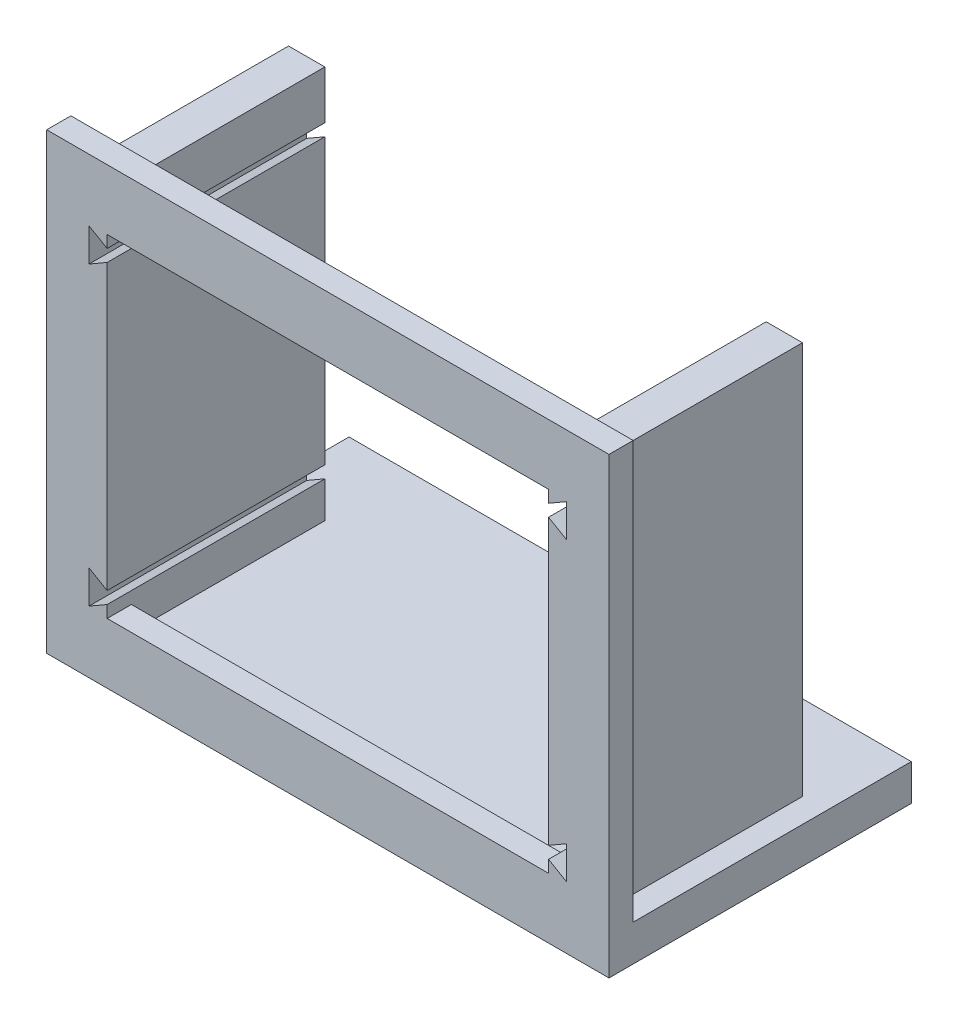
SolidWorks part; units mm, degrees
ref_plane "Front Plane" through (0, 0, 0) normal (0, 0, 1) x (1, 0, 0)
ref_plane "Top Plane" through (0, 0, 0) normal (0, 1, 0) x (1, 0, 0)
ref_plane "Right Plane" through (0, 0, 0) normal (1, 0, 0) x (0, 0, -1)
sketch "Sketch2" plane through (0, 0, 0) normal (0, 1, 0) x (1, 0, 0)
  line L1 (-100, 75) -> (100, 75)
  line L2 (-100, 75) -> (-100, -75)
  line L3 (-100, -75) -> (100, -75)
  line L4 (100, 75) -> (100, -75)
  line L5 (-100, 75) -> (100, -75) construction
  line L6 (-100, -75) -> (100, 75) construction
  point P0 (0, 0)
  dimension "D1" = 200
  dimension "D2" = 150
extrude "Boss-Extrude1" add sketch "Sketch2" along normal blind 80
fillet "Fillet1" radius 10 4 edges at (-100, 40, -75) (100, 40, -75) (100, 40, 75) (-100, 40, 75)
shell "Shell1" thickness 2
sketch "Sketch5" plane through (0, 0, 75) normal (0, 0, 1) x (1, 0, 0)
  line L1 (-18.25, 44.5) -> (18.25, 44.5)
  line L2 (-18.25, 44.5) -> (-18.25, 17)
  line L3 (-18.25, 17) -> (18.25, 17)
  line L4 (18.25, 44.5) -> (18.25, 17)
  line L5 (-18.25, 43.5) -> (-19.75, 44.366)
  line L6 (-19.75, 44.366) -> (-19.75, 41.634)
  line L7 (-19.75, 41.634) -> (-18.25, 42.5)
  line L8 (-18.25, 42.5) -> (-18.25, 43.5)
  line L9 (0, 44.5) -> (0, 17) construction
  line L10 (-18.25, 30.75) -> (18.25, 30.75) construction
  line L11 (-19.75, 19.866) -> (-18.25, 19)
  line L12 (-19.75, 17.134) -> (-19.75, 19.866)
  line L13 (-18.25, 18) -> (-19.75, 17.134)
  line L14 (-18.25, 19) -> (-18.25, 18)
  line L15 (19.75, 17.134) -> (19.75, 19.866)
  line L16 (18.25, 18) -> (19.75, 17.134)
  line L17 (18.25, 19) -> (18.25, 18)
  line L18 (19.75, 19.866) -> (18.25, 19)
  line L19 (19.75, 41.634) -> (18.25, 42.5)
  line L20 (19.75, 44.366) -> (19.75, 41.634)
  line L21 (18.25, 43.5) -> (19.75, 44.366)
  line L22 (18.25, 42.5) -> (18.25, 43.5)
  line L23 (-90, 15) -> (90, 15) construction
  point P4 (0, 17)
  dimension "D1" = 36.5
  dimension "D2" = 27.5
  dimension "D3" = 60
  dimension "D4" = 60
  dimension "D5" = 1
  dimension "D6" = 1
  dimension "D7" = 1.5
  dimension "D8" = 2
extrude "Cut-Extrude1" cut sketch "Sketch5" against normal up to surface (2 mm away) contours L1 L4 L3 L2 | L7 L8 L5 L6 | L12 L11 L14 L13 | L20 L19 L22 L21 | L15 L18 L17 L16 up to face at (0, 47.5, 73)
sketch "Sketch6" plane through (0, 0, 73) normal (0, 0, -1) x (-1, 0, 0)
  line L0 (18.25, 15) -> (21.25, 15)
  line L2 (-21.25, 47.5) -> (-21.25, 15)
  line L4 (19.75, 44.366) -> (18.25, 43.5)
  line L5 (19.75, 41.634) -> (19.75, 44.366)
  line L6 (18.25, 42.5) -> (19.75, 41.634)
  line L7 (18.25, 43.5) -> (18.25, 42.5)
  line L8 (19.75, 44.366) -> (18.25, 43.5)
  line L9 (19.75, 41.634) -> (19.75, 44.366)
  line L10 (18.25, 42.5) -> (19.75, 41.634)
  line L12 (18.25, 44.5) -> (-18.25, 44.5)
  line L13 (-18.25, 44.5) -> (-18.25, 17)
  line L14 (-18.25, 17) -> (18.25, 17)
  line L15 (18.25, 17) -> (18.25, 44.5)
  line L17 (-18.25, 47.5) -> (-18.25, 43.5)
  line L19 (18.25, 15) -> (18.25, 18)
  line L20 (-19.75, 41.634) -> (-18.25, 42.5)
  line L21 (-18.25, 42.5) -> (-18.25, 43.5)
  line L22 (-18.25, 43.5) -> (-19.75, 44.366)
  line L23 (-19.75, 44.366) -> (-19.75, 41.634)
  line L24 (-19.75, 41.634) -> (-18.25, 42.5)
  line L26 (-18.25, 43.5) -> (-19.75, 44.366)
  line L27 (-19.75, 44.366) -> (-19.75, 41.634)
  line L28 (-19.75, 19.866) -> (-19.75, 17.134)
  line L29 (-18.25, 19) -> (-19.75, 19.866)
  line L30 (-18.25, 18) -> (-18.25, 19)
  line L31 (-19.75, 17.134) -> (-18.25, 18)
  line L32 (-19.75, 19.866) -> (-19.75, 17.134)
  line L33 (-18.25, 19) -> (-19.75, 19.866)
  line L35 (-19.75, 17.134) -> (-18.25, 18)
  line L36 (19.75, 19.866) -> (18.25, 19)
  line L37 (18.25, 19) -> (18.25, 18)
  line L38 (18.25, 18) -> (19.75, 17.134)
  line L39 (19.75, 17.134) -> (19.75, 19.866)
  line L40 (19.75, 19.866) -> (18.25, 19)
  line L42 (18.25, 18) -> (19.75, 17.134)
  line L43 (19.75, 17.134) -> (19.75, 19.866)
  line L44 (21.25, 47.5) -> (21.25, 15)
  line L45 (-18.25, 15) -> (-21.25, 15)
  line L46 (-18.25, 42.5) -> (-18.25, 19)
  line L47 (18.25, 43.5) -> (18.25, 47.5)
  line L48 (18.25, 19) -> (18.25, 42.5)
  line L49 (-18.25, 18) -> (-18.25, 15)
  line L50 (21.25, 47.5) -> (18.25, 47.5)
  line L51 (-21.25, 47.5) -> (-18.25, 47.5)
  line L54 (18.25, 44.5) -> (-18.25, 44.5) construction
  line L55 (90, 15) -> (-90, 15) construction
  dimension "D6" = 3
  dimension "D7" = 3
  dimension "D8" = 3
  dimension "D1" = 0
  dimension "D2" = 0
  dimension "D3" = 0
  dimension "D4" = 0
  dimension "D5" = 0
extrude "Boss-Extrude2" add sketch "Sketch6" along normal blind 16
sketch "Sketch7" plane through (100, 0, 0) normal (1, 0, 0) x (0, 0, -1)
  line L0 (-65, 15) -> (65, 15) construction
  line L1 (-18.25, 44.5) -> (18.25, 44.5)
  line L2 (-18.25, 44.5) -> (-18.25, 17)
  line L3 (-18.25, 17) -> (18.25, 17)
  line L4 (18.25, 44.5) -> (18.25, 17)
  line L5 (-18.25, 43.5) -> (-19.75, 44.366)
  line L6 (-19.75, 44.366) -> (-19.75, 41.634)
  line L7 (-19.75, 41.634) -> (-18.25, 42.5)
  line L8 (-18.25, 42.5) -> (-18.25, 43.5)
  line L9 (0, 44.5) -> (0, 17) construction
  line L10 (-18.25, 30.75) -> (18.25, 30.75) construction
  line L11 (-19.75, 19.866) -> (-18.25, 19)
  line L12 (-19.75, 17.134) -> (-19.75, 19.866)
  line L13 (-18.25, 18) -> (-19.75, 17.134)
  line L14 (-18.25, 19) -> (-18.25, 18)
  line L15 (19.75, 17.134) -> (19.75, 19.866)
  line L16 (18.25, 18) -> (19.75, 17.134)
  line L17 (18.25, 19) -> (18.25, 18)
  line L18 (19.75, 19.866) -> (18.25, 19)
  line L19 (19.75, 41.634) -> (18.25, 42.5)
  line L20 (19.75, 44.366) -> (19.75, 41.634)
  line L21 (18.25, 43.5) -> (19.75, 44.366)
  line L22 (18.25, 42.5) -> (18.25, 43.5)
  dimension "D1" = 36.5
  dimension "D2" = 27.5
  dimension "D3" = 60
  dimension "D4" = 60
  dimension "D5" = 1
  dimension "D6" = 1
  dimension "D7" = 1.5
  dimension "D8" = 2
extrude "Cut-Extrude2" cut sketch "Sketch7" against normal blind 2 contours L1 L4 L3 L2 | L7 L8 L5 L6 | L12 L11 L14 L13 | L20 L19 L22 L21 | L15 L18 L17 L16
sketch "Sketch8" plane through (98, 0, 0) normal (-1, 0, 0) x (0, 0, 1)
  line L0 (65, 15) -> (-65, 15) construction
  line L1 (-21.25, 47.5) -> (-18.25, 47.5)
  line L2 (-21.25, 47.5) -> (-21.25, 15)
  line L3 (-21.25, 15) -> (-18.25, 15)
  line L4 (19.75, 44.366) -> (18.25, 43.5)
  line L5 (19.75, 41.634) -> (19.75, 44.366)
  line L6 (18.25, 42.5) -> (19.75, 41.634)
  line L7 (18.25, 43.5) -> (18.25, 42.5)
  line L8 (19.75, 44.366) -> (18.25, 43.5)
  line L9 (19.75, 41.634) -> (19.75, 44.366)
  line L10 (18.25, 42.5) -> (19.75, 41.634)
  line L20 (-19.75, 41.634) -> (-18.25, 42.5)
  line L21 (-18.25, 42.5) -> (-18.25, 43.5)
  line L22 (-18.25, 43.5) -> (-19.75, 44.366)
  line L23 (-19.75, 44.366) -> (-19.75, 41.634)
  line L24 (-19.75, 41.634) -> (-18.25, 42.5)
  line L26 (-18.25, 43.5) -> (-19.75, 44.366)
  line L27 (-19.75, 44.366) -> (-19.75, 41.634)
  line L28 (-19.75, 19.866) -> (-19.75, 17.134)
  line L29 (-18.25, 19) -> (-19.75, 19.866)
  line L30 (-18.25, 18) -> (-18.25, 19)
  line L31 (-19.75, 17.134) -> (-18.25, 18)
  line L32 (-19.75, 19.866) -> (-19.75, 17.134)
  line L33 (-18.25, 19) -> (-19.75, 19.866)
  line L35 (-19.75, 17.134) -> (-18.25, 18)
  line L36 (19.75, 19.866) -> (18.25, 19)
  line L37 (18.25, 19) -> (18.25, 18)
  line L38 (18.25, 18) -> (19.75, 17.134)
  line L39 (19.75, 17.134) -> (19.75, 19.866)
  line L40 (19.75, 19.866) -> (18.25, 19)
  line L42 (18.25, 18) -> (19.75, 17.134)
  line L43 (19.75, 17.134) -> (19.75, 19.866)
  line L44 (-18.25, 47.5) -> (-18.25, 43.5)
  line L46 (-18.25, 42.5) -> (-18.25, 19) construction
  line L47 (18.25, 44.5) -> (-18.25, 44.5) construction
  line L48 (-18.25, 42.5) -> (-18.25, 19)
  line L49 (-18.25, 18) -> (-18.25, 15)
  line L50 (18.25, 42.5) -> (18.25, 19) construction
  line L51 (18.25, 47.5) -> (21.25, 47.5)
  line L52 (18.25, 47.5) -> (18.25, 43.5)
  line L53 (18.25, 15) -> (21.25, 15)
  line L54 (21.25, 47.5) -> (21.25, 15)
  line L55 (18.25, 42.5) -> (18.25, 19)
  line L56 (18.25, 18) -> (18.25, 15)
  dimension "D6" = 3
  dimension "D7" = 3
  dimension "D2" = 3
  dimension "D1" = 0
  dimension "D3" = 0
  dimension "D4" = 0
  dimension "D5" = 0
extrude "Boss-Extrude3" add sketch "Sketch8" along normal blind 16
sketch "Sketch10" plane through (-100, 0, 0) normal (-1, 0, 0) x (0, 0, 1)
  line L1 (-18.25, 44.5) -> (18.25, 44.5)
  line L2 (-18.25, 44.5) -> (-18.25, 17)
  line L3 (-18.25, 17) -> (18.25, 17)
  line L4 (18.25, 44.5) -> (18.25, 17)
  line L5 (-18.25, 43.5) -> (-19.75, 44.366)
  line L6 (-19.75, 44.366) -> (-19.75, 41.634)
  line L7 (-19.75, 41.634) -> (-18.25, 42.5)
  line L8 (-18.25, 42.5) -> (-18.25, 43.5)
  line L9 (0, 44.5) -> (0, 17) construction
  line L10 (-18.25, 30.75) -> (18.25, 30.75) construction
  line L11 (-19.75, 19.866) -> (-18.25, 19)
  line L12 (-19.75, 17.134) -> (-19.75, 19.866)
  line L13 (-18.25, 18) -> (-19.75, 17.134)
  line L14 (-18.25, 19) -> (-18.25, 18)
  line L15 (19.75, 17.134) -> (19.75, 19.866)
  line L16 (18.25, 18) -> (19.75, 17.134)
  line L17 (18.25, 19) -> (18.25, 18)
  line L18 (19.75, 19.866) -> (18.25, 19)
  line L19 (19.75, 41.634) -> (18.25, 42.5)
  line L20 (19.75, 44.366) -> (19.75, 41.634)
  line L21 (18.25, 43.5) -> (19.75, 44.366)
  line L22 (18.25, 42.5) -> (18.25, 43.5)
  line L23 (-65, 15) -> (65, 15) construction
  dimension "D1" = 36.5
  dimension "D2" = 27.5
  dimension "D3" = 60
  dimension "D4" = 60
  dimension "D5" = 1
  dimension "D6" = 1
  dimension "D7" = 1.5
  dimension "D8" = 2
extrude "Cut-Extrude4" cut sketch "Sketch10" against normal blind 2 contours L1 L4 L3 L2 | L7 L8 L5 L6 | L12 L11 L14 L13 | L20 L19 L22 L21 | L15 L18 L17 L16
sketch "Sketch11" plane through (-98, 0, 0) normal (1, 0, 0) x (0, 0, -1)
  line L1 (-18.25, 42.5) -> (-18.25, 19) construction
  line L2 (-18.25, 47.5) -> (-21.25, 47.5)
  line L3 (-18.25, 47.5) -> (-18.25, 43.5)
  line L4 (19.75, 44.366) -> (18.25, 43.5)
  line L5 (19.75, 41.634) -> (19.75, 44.366)
  line L6 (18.25, 42.5) -> (19.75, 41.634)
  line L7 (18.25, 43.5) -> (18.25, 42.5)
  line L8 (19.75, 44.366) -> (18.25, 43.5)
  line L9 (19.75, 41.634) -> (19.75, 44.366)
  line L10 (18.25, 42.5) -> (19.75, 41.634)
  line L20 (-19.75, 41.634) -> (-18.25, 42.5)
  line L21 (-18.25, 42.5) -> (-18.25, 43.5)
  line L22 (-18.25, 43.5) -> (-19.75, 44.366)
  line L23 (-19.75, 44.366) -> (-19.75, 41.634)
  line L24 (-19.75, 41.634) -> (-18.25, 42.5)
  line L26 (-18.25, 43.5) -> (-19.75, 44.366)
  line L27 (-19.75, 44.366) -> (-19.75, 41.634)
  line L28 (-19.75, 19.866) -> (-19.75, 17.134)
  line L29 (-18.25, 19) -> (-19.75, 19.866)
  line L30 (-18.25, 18) -> (-18.25, 19)
  line L31 (-19.75, 17.134) -> (-18.25, 18)
  line L32 (-19.75, 19.866) -> (-19.75, 17.134)
  line L33 (-18.25, 19) -> (-19.75, 19.866)
  line L35 (-19.75, 17.134) -> (-18.25, 18)
  line L36 (19.75, 19.866) -> (18.25, 19)
  line L37 (18.25, 19) -> (18.25, 18)
  line L38 (18.25, 18) -> (19.75, 17.134)
  line L39 (19.75, 17.134) -> (19.75, 19.866)
  line L40 (19.75, 19.866) -> (18.25, 19)
  line L42 (18.25, 18) -> (19.75, 17.134)
  line L43 (19.75, 17.134) -> (19.75, 19.866)
  line L44 (-18.25, 15) -> (-21.25, 15)
  line L45 (-21.25, 47.5) -> (-21.25, 15)
  line L46 (65, 15) -> (-65, 15) construction
  line L47 (18.25, 44.5) -> (-18.25, 44.5) construction
  line L48 (-18.25, 42.5) -> (-18.25, 19)
  line L49 (-18.25, 18) -> (-18.25, 15)
  line L50 (18.25, 42.5) -> (18.25, 19) construction
  line L51 (18.25, 47.5) -> (21.25, 47.5)
  line L52 (18.25, 47.5) -> (18.25, 43.5)
  line L53 (18.25, 15) -> (21.25, 15)
  line L54 (21.25, 47.5) -> (21.25, 15)
  line L55 (18.25, 42.5) -> (18.25, 19)
  line L56 (18.25, 18) -> (18.25, 15)
  dimension "D2" = 3
  dimension "D6" = 3
  dimension "D7" = 3
  dimension "D1" = 0
  dimension "D3" = 0
  dimension "D4" = 0
  dimension "D5" = 0
extrude "Boss-Extrude4" add sketch "Sketch11" along normal blind 16
sketch "Sketch13" plane through (0, 0, 75) normal (0, 0, 1) x (1, 0, 0)
  line L0 (-18.25, 30.75) -> (18.25, 30.75) construction
  line L1 (-18.25, 30.75) -> (18.25, 30.75) construction
  line L2 (41, 39.3) -> (39.5, 40.166)
  line L3 (41, 40.3) -> (79, 40.3)
  line L4 (41, 40.3) -> (41, 21.2)
  line L5 (41, 21.2) -> (79, 21.2)
  line L6 (79, 40.3) -> (79, 21.2)
  line L7 (39.5, 40.166) -> (39.5, 37.434)
  line L8 (39.5, 37.434) -> (41, 38.3)
  line L9 (41, 39.3) -> (41, 38.3)
  line L10 (60, 40.3) -> (60, 21.2) construction
  line L11 (41, 22.2) -> (39.5, 21.334)
  line L12 (39.5, 21.334) -> (39.5, 24.066)
  line L13 (39.5, 24.066) -> (41, 23.2)
  line L14 (41, 22.2) -> (41, 23.2)
  line L15 (79, 22.2) -> (79, 23.2)
  line L16 (80.5, 24.066) -> (79, 23.2)
  line L17 (80.5, 21.334) -> (80.5, 24.066)
  line L18 (79, 22.2) -> (80.5, 21.334)
  line L19 (79, 39.3) -> (80.5, 40.166)
  line L20 (80.5, 40.166) -> (80.5, 37.434)
  line L21 (80.5, 37.434) -> (79, 38.3)
  line L22 (79, 39.3) -> (79, 38.3)
  point P6 (41, 30.75)
  point P7 (60, 21.2)
  dimension "D1" = 19.1
  dimension "D2" = 38
  dimension "D3" = 60
  dimension "D4" = 60
  dimension "D5" = 60
  dimension "D6" = 1
  dimension "D7" = 1
  dimension "D8" = 1.5
extrude "Cut-Extrude5" cut sketch "Sketch13" against normal up to surface (2 mm away) contours L3 L6 L5 L4 | L7 L8 L9 L2 | L12 L13 L14 L11 | L17 L16 L15 L18 | L20 L21 L22 L19 up to face at (0, 41.5833, 73)
sketch "Sketch14" plane through (0, 0, 73) normal (0, 0, -1) x (-1, 0, 0)
  line L0 (-21.25, 15) -> (-90, 15) construction
  line L1 (-79, 43.3) -> (-82, 43.3)
  line L2 (-79, 43.3) -> (-79, 39.3)
  line L3 (-79, 15) -> (-82, 15)
  line L6 (-82, 43.3) -> (-82, 15)
  line L12 (-39.5, 40.166) -> (-41, 39.3)
  line L13 (-39.5, 37.434) -> (-39.5, 40.166)
  line L14 (-41, 38.3) -> (-39.5, 37.434)
  line L15 (-41, 39.3) -> (-41, 38.3)
  line L16 (-39.5, 40.166) -> (-41, 39.3)
  line L17 (-39.5, 37.434) -> (-39.5, 40.166)
  line L18 (-41, 38.3) -> (-39.5, 37.434)
  line L20 (-79, 39.3) -> (-80.5, 40.166)
  line L21 (-80.5, 40.166) -> (-80.5, 37.434)
  line L22 (-80.5, 37.434) -> (-79, 38.3)
  line L23 (-79, 38.3) -> (-79, 39.3)
  line L24 (-79, 39.3) -> (-80.5, 40.166)
  line L25 (-80.5, 40.166) -> (-80.5, 37.434)
  line L26 (-80.5, 37.434) -> (-79, 38.3)
  line L28 (-79, 22.2) -> (-79, 23.2)
  line L29 (-79, 23.2) -> (-80.5, 24.066)
  line L30 (-80.5, 24.066) -> (-80.5, 21.334)
  line L31 (-80.5, 21.334) -> (-79, 22.2)
  line L33 (-79, 23.2) -> (-80.5, 24.066)
  line L34 (-80.5, 24.066) -> (-80.5, 21.334)
  line L35 (-80.5, 21.334) -> (-79, 22.2)
  line L36 (-39.5, 21.334) -> (-39.5, 24.066)
  line L37 (-39.5, 24.066) -> (-41, 23.2)
  line L38 (-41, 23.2) -> (-41, 22.2)
  line L39 (-41, 22.2) -> (-39.5, 21.334)
  line L40 (-39.5, 21.334) -> (-39.5, 24.066)
  line L41 (-39.5, 24.066) -> (-41, 23.2)
  line L43 (-41, 22.2) -> (-39.5, 21.334)
  line L44 (-41, 40.3) -> (-79, 40.3) construction
  line L45 (-41, 43.3) -> (-38, 43.3)
  line L46 (-41, 43.3) -> (-41, 39.3)
  line L47 (-41, 15) -> (-38, 15)
  line L48 (-38, 43.3) -> (-38, 15)
  line L49 (-79, 38.3) -> (-79, 23.2) construction
  line L50 (-41, 38.3) -> (-41, 23.2) construction
  line L51 (-79, 38.3) -> (-79, 23.2)
  line L52 (-79, 22.2) -> (-79, 15)
  line L53 (-41, 38.3) -> (-41, 23.2)
  line L54 (-41, 22.2) -> (-41, 15)
  dimension "D1" = 3
  dimension "D6" = 3
  dimension "D7" = 3
  dimension "D2" = 0
  dimension "D3" = 0
  dimension "D4" = 0
  dimension "D5" = 0
extrude "Boss-Extrude5" add sketch "Sketch14" along normal blind 13.5
sketch "Sketch15" plane through (38, 0, 0) normal (-1, 0, 0) x (0, 0, 1)
  line L4 (59.5, 15) -> (59.5, 43.3) construction
  line L5 (73, 15) -> (73, 43.3) construction
  line L6 (59.5, 43.3) -> (59.5, 15) construction
  line L7 (59.5, 37.434) -> (75, 37.434) construction
  line L8 (59.5, 24.066) -> (75, 24.066) construction
  line L12 (72, 26.066) -> (72, 35.434)
  line L13 (72, 35.434) -> (61.5, 35.434)
  line L14 (61.5, 35.434) -> (61.5, 26.066)
  line L15 (61.5, 26.066) -> (72, 26.066)
  dimension "D1" = 2
  dimension "D2" = 1
  dimension "D3" = 2
  dimension "D4" = 2
extrude "Cut-Extrude6" cut sketch "Sketch15" against normal up to surface (3 mm away) up to face at (41, 30.75, 67.25)
sketch "Sketch18" plane through (0, 0, 0) normal (1, 0, 0) x (0, 0, -1)
  line L0 (0, 0) -> (0, 10) construction
  line L3 (-42.5, 0) -> (-70, 0)
  line L4 (-70, 0) -> (-47.5, 10)
  line L5 (-47.5, 10) -> (-42.5, 10)
  line L6 (-42.5, 10) -> (-42.5, 0)
  line L7 (65, 0) -> (-65, 0) construction
  dimension "D1" = 10
  dimension "D2" = 70
  dimension "D3" = 5
  dimension "D4" = 42.5
revolve "Cut-Revolve1" cut sketch "Sketch18" angle 360 about L0
sketch "Sketch20" plane through (0, 0, 0) normal (0, -1, 0) x (1, 0, 0)
  circle A0 centre (0, -42.5) radius 8
  circle A1 centre (0, 0) radius 42.5 construction
  circle A2 centre (0, 0) radius 42.5 construction
  dimension "D1" = 16
extrude "Cut-Extrude8" cut sketch "Sketch20" against normal up to surface (15 mm away) up to face at (12, 15, 26.25)
sketch "Sketch21" plane through (0, 0, 75) normal (0, 0, 1) x (1, 0, 0)
  line L0 (18.25, 42.5) -> (18.25, 19) construction
  line L1 (-23.25, 49.5) -> (23.25, 49.5)
  line L2 (-23.25, 49.5) -> (-23.25, 12)
  line L3 (-23.25, 12) -> (23.25, 12)
  line L4 (23.25, 49.5) -> (23.25, 12)
  line L5 (-23.25, 49.5) -> (23.25, 12) construction
  line L6 (-23.25, 12) -> (23.25, 49.5) construction
  line L7 (18.25, 42.5) -> (18.25, 19) construction
  line L8 (-18.25, 15) -> (18.25, 15) construction
  point P0 (0, 30.75)
  point P9 (18.25, 30.75)
  dimension "D1" = 3
  dimension "D2" = 5
split "Split1" trim tools "Sketch21" bodies to split 113 resulting bodies 114 115
sketch "Sketch22" plane through (0, 15, 0) normal (0, 1, 0) x (1, 0, 0)
  line L0 (23.25, -73) -> (23.25, 73) construction
  line L1 (-23.25, -75) -> (23.25, -75)
  line L2 (-23.25, -75) -> (-23.25, -50)
  line L3 (-23.25, -50) -> (23.25, -50)
  line L4 (23.25, -75) -> (23.25, -50)
  dimension "D1" = 25
split "Split2" trim tools "Sketch22" bodies to split 115 resulting bodies 116 117
delete or keep bodies "Body-Delete/Keep 1" type delete bodies bodies 116 114
